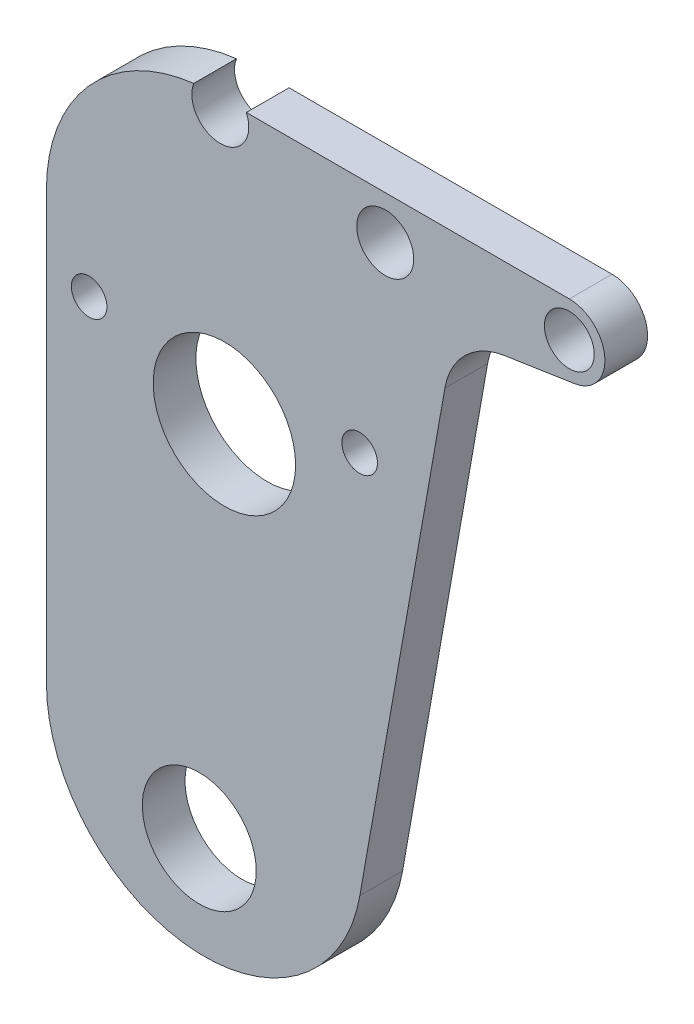
SolidWorks part; units mm, degrees
ref_plane "Front Plane" through (0, 0, 0) normal (0, 0, 1) x (1, 0, 0)
ref_plane "Top Plane" through (0, 0, 0) normal (0, 1, 0) x (1, 0, 0)
ref_plane "Right Plane" through (0, 0, 0) normal (1, 0, 0) x (0, 0, -1)
sketch "Sketch3" plane through (0, 0, 0) normal (0, 0, 1) x (1, 0, 0)
  line L0 (-12.5, -15) -> (-12.5, 15)
  line L1 (-0.7757, 26.7243) -> (24.2243, 26.7243)
  line L2 (24.6001, 21.7527) -> (19.6569, 21.001)
  line L3 (15.4845, 16.9261) -> (9.5155, -16.9261)
  line L4 (-12.5, 0) -> (12.5, 0) construction
  line L5 (-2.3747, -26.0498) -> (-1.408, -15) construction
  arc A0 (-12.5, 15) -> (-0.7757, 26.7243) centre (-0.7757, 15) cw
  arc A1 (24.2243, 26.7243) -> (24.6001, 21.7527) centre (24.2243, 24.2243) cw
  arc A2 (19.6569, 21.001) -> (15.4845, 16.9261) centre (20.4086, 16.0579) ccw
  arc A3 (-12.5, -15) -> (9.5155, -16.9261) centre (-1.408, -15) ccw
  circle A4 centre (-1.7646, -19.0764) radius 4
  point P18 (-0.4776, 27.0224)
  dimension "D3" = 10
  dimension "D8" = 5
  dimension "D10" = 8
  dimension "D4" = 2.5
  dimension "D1" = 25
  dimension "D2" = 30
  dimension "D5" = 25
  dimension "D6" = 5
  dimension "D9" = 7
extrude "Boss-Extrude4" add sketch "Sketch3" along normal blind 3
sketch "Sketch5" plane through (0, 0, 3) normal (0, 0, 1) x (1, 0, 0)
  line L0 (-9.5, 10) -> (9.5, 10) construction
  line L1 (0, 10) -> (0, 7) construction
  line L2 (0, 7) -> (0, 0) construction
  circle A0 centre (-9.5, 10) radius 1.25
  circle A1 centre (9.5, 10) radius 1.25
  circle A2 centre (0, 7) radius 5
  dimension "D2" = 10
  dimension "D3" = 2.5
  dimension "D1" = 19
  dimension "D4" = 3
  dimension "D5" = 7
extrude "Cut-Extrude2" cut sketch "Sketch5" against normal through all
sketch "Sketch6" plane through (0, 0, 3) normal (0, 0, 1) x (1, 0, 0)
  circle A0 centre (24.2243, 24.2243) radius 1.75
  dimension "D1" = 3.5
extrude "Cut-Extrude3" cut sketch "Sketch6" against normal through all
sketch "Sketch8" plane through (0, 0, 3) normal (0, 0, 1) x (1, 0, 0)
  circle A0 centre (11.2954, 23.6809) radius 2 construction
  circle A1 centre (-0.2894, 25.9197) radius 2 construction
  circle A2 centre (11.2954, 23.6809) radius 2
  circle A3 centre (-0.2894, 25.9197) radius 2
extrude "Cut-Extrude4" cut sketch "Sketch8" against normal through all
